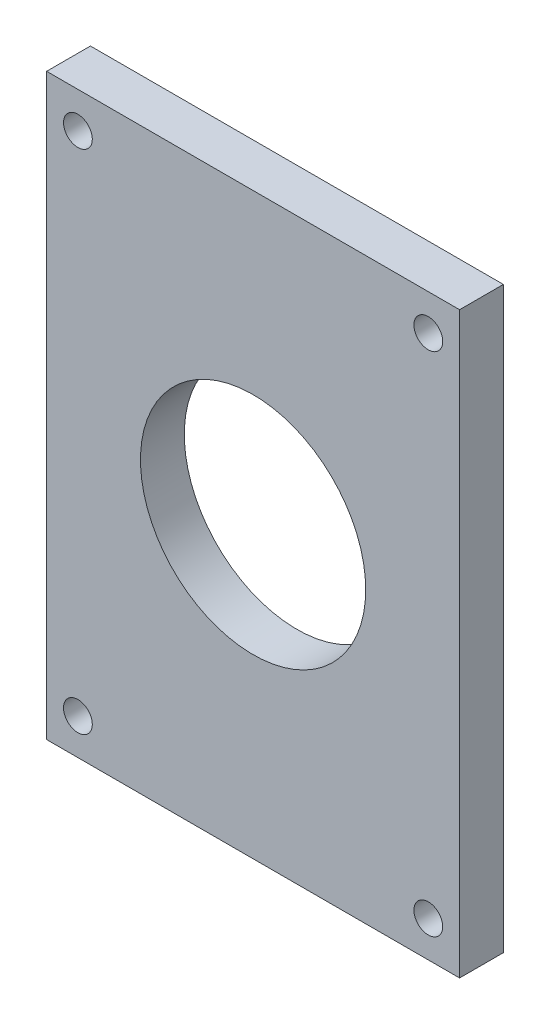
SolidWorks part; units mm, degrees
ref_plane "Front Plane" through (0, 0, 0) normal (0, 0, 1) x (1, 0, 0)
ref_plane "Top Plane" through (0, 0, 0) normal (0, 1, 0) x (1, 0, 0)
ref_plane "Right Plane" through (0, 0, 0) normal (1, 0, 0) x (0, 0, -1)
sketch "Sketch1" plane through (0, 0, 0) normal (0, 0, 1) x (1, 0, 0)
  line L0 (-33, -46.25) -> (33, -46.25)
  line L1 (33, -46.25) -> (33, 46.25)
  line L2 (33, 46.25) -> (-33, 46.25)
  line L3 (-33, 46.25) -> (-33, -46.25)
  circle A0 centre (0, 0) radius 18
  circle A1 centre (-28, -40.5) radius 2.3
  circle A2 centre (-28, 40.5) radius 2.3
  circle A3 centre (28, -40.5) radius 2.3
  circle A4 centre (28, 40.5) radius 2.3
extrude "Upper bearing plate" add sketch "Sketch1" along normal blind 7 from offset 58
